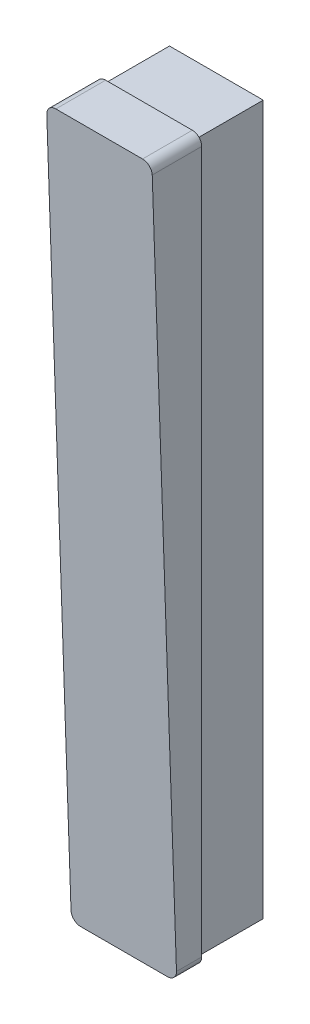
SolidWorks part; units mm, degrees
ref_plane "Front Plane" through (0, 0, 0) normal (0, 0, 1) x (1, 0, 0)
ref_plane "Top Plane" through (0, 0, 0) normal (0, 1, 0) x (1, 0, 0)
ref_plane "Right Plane" through (0, 0, 0) normal (1, 0, 0) x (0, 0, -1)
ref_plane "Plane1" through (-28.575, 0, 0) normal (-1, 0, 0) x (0, -1, 0)
sketch "Sketch1" plane through (-28.575, 0, 0) normal (-1, 0, 0) x (0, -1, 0)
  line L0 (195.2625, 13.4937) -> (-195.2625, 26.9875)
  line L1 (-195.2625, 26.9875) -> (-195.2625, 0)
  line L2 (-195.2625, 0) -> (195.2625, 0)
  line L3 (195.2625, 0) -> (195.2625, 13.4937)
  point P4 (0, 0)
  dimension "D1" = 390.525
  dimension "D2" = 26.9875
  dimension "D3" = 13.4937
extrude "Boss-Extrude1" add sketch "Sketch1" against normal blind 57.15
sketch "Sketch15" plane through (0, 0, 0) normal (0, 0, -1) x (-1, 0, 0)
  line L0 (25.4, -192.0875) -> (-25.4, -192.0875)
  line L1 (-25.4, -192.0875) -> (-25.4, 192.0875)
  line L2 (-25.4, 192.0875) -> (25.4, 192.0875)
  line L3 (25.4, 192.0875) -> (25.4, -192.0875)
  line L5 (-25.4, 192.0875) -> (25.4, -192.0875) construction
  line L6 (-25.4, -192.0875) -> (25.4, 192.0875) construction
  dimension "D1" = 384.175
  dimension "D2" = 50.8
extrude "Boss-Extrude7" add sketch "Sketch15" along normal blind 36.5125
hole_wizard "M8 Clearance Hole1" positions "Sketch23" profile "Sketch22" hole size "M8" standard "ANSI Metric"
sketch "Sketch23" plane through (0, 0, -36.5125) normal (0, 0, -1) x (-1, 0, 0)
  line L0 (25.4, 192.0875) -> (-25.4, 192.0875) construction
  line L1 (0, -122.2375) -> (0, 100.0125) construction
  line L3 (25.4, -192.0875) -> (25.4, 192.0875) construction
  line L4 (-25.4, 192.0875) -> (-25.4, -192.0875) construction
  point P0 (0, 100.0125)
  point P1 (0, -122.2375)
  dimension "D1" = 222.25
  dimension "D2" = 92.075
sketch "Sketch22" plane through (0, 100.0125, -36.5125) normal (1, 0, 0) x (0, 1, 0)
  line L0 (0, 0) -> (0, 26.8921)
  line L1 (0, 26.8921) -> (4.2164, 24.3586)
  line L2 (4.2164, 24.3586) -> (4.2164, 0)
  line L5 (4.2164, 0) -> (0, 0)
  line L10 (0, 26.8921) -> (-4.2164, 24.3586) construction
  line L11 (0, -6.35) -> (0, 107.95) construction
  dimension "Hole Dia." = 8.4328
  dimension "Hole Depth" = 24.3586
  dimension "Drill Angle" = 118
sketch3d "3DSketch1"
  line L0 (0, 144.4625, -36.5125) -> (0, -166.6875, -36.5125) construction
  line L1 (-25.4, 192.0875, -36.5125) -> (25.4, 192.0875, -36.5125) construction
  line L2 (25.4, -192.0875, -36.5125) -> (-25.4, -192.0875, -36.5125) construction
  point P0 (0, 144.4625, -36.5125)
  point P1 (0, -166.6875, -36.5125)
  dimension "D1" = 47.625
  dimension "D2" = 25.4
fillet "Fillet1" radius 5.08 4 edges at (-28.575, 195.2625, 13.4937) (-28.575, -195.2625, 6.7469) (28.575, 195.2625, 13.4937) (28.575, -195.2625, 6.7469)
hole_wizard "3/4 NPT Tapped Hole1" positions "Sketch26" profile "Sketch27" size "3/4" standard "ANSI Inch"
sketch "Sketch26" plane through (0, 0, -36.5125) normal (0, 0, -1) x (-1, 0, 0)
  point P0 (0, 144.4625)
  point P3 (0, -166.6875)
sketch "Sketch27" plane through (0, 144.4625, -36.5125) normal (1, 0, 0) x (0, 1, 0)
  line L0 (0, 0) -> (0, 30.0276)
  line L1 (11.5062, 23.114) -> (0, 30.0276)
  line L2 (-11.5062, 23.114) -> (0, 30.0276) construction
  line L3 (11.5062, 23.114) -> (11.5062, 14.0462)
  line L4 (11.5062, 14.0462) -> (12.9142, 14.0462)
  line L5 (12.9142, 14.0462) -> (13.3348, 0)
  line L6 (-12.9142, 14.0462) -> (-13.3348, 0) construction
  line L7 (13.3348, 0) -> (0, 0)
  line L8 (0, -6.35) -> (0, 107.95) construction
  line L11 (-11.5062, 14.0462) -> (-12.9142, 14.0462) construction
  dimension "Tap Drill Dia." = 23.0124
  dimension "Tap Drill Depth" = 23.114
  dimension "Thread Dia." = 26.6695
  dimension "Thread Angle" = 3.43
  dimension "Thread Depth" = 14.0462
  dimension "Drill Angle" = 118
